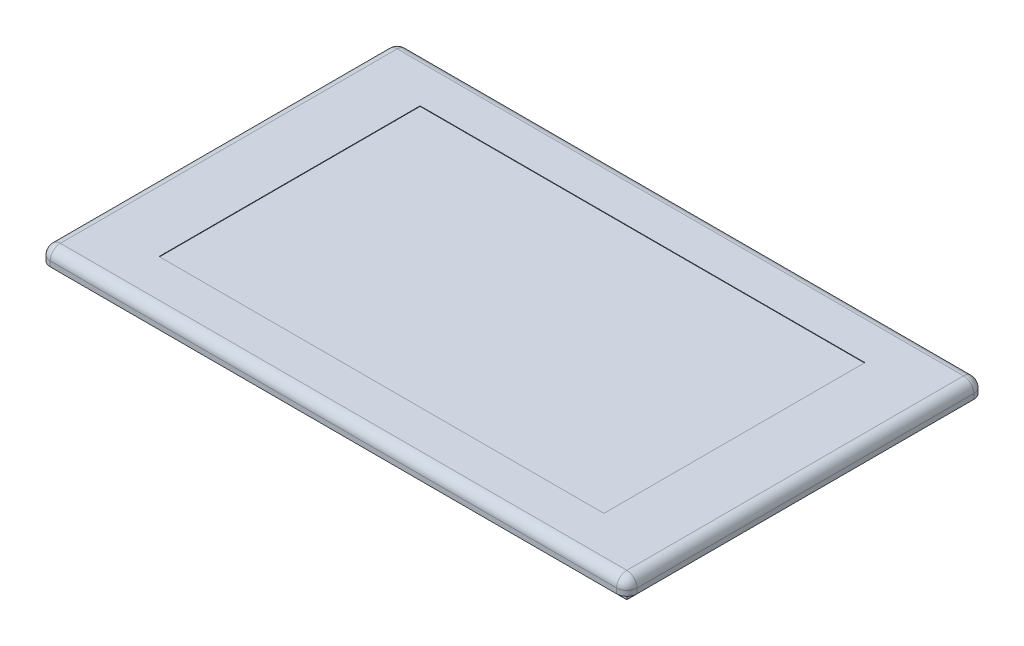
SolidWorks part; units mm, degrees
ref_plane "Front Plane" through (0, 0, 0) normal (0, 0, 1) x (1, 0, 0)
ref_plane "Top Plane" through (0, 0, 0) normal (0, 1, 0) x (1, 0, 0)
ref_plane "Right Plane" through (0, 0, 0) normal (1, 0, 0) x (0, 0, -1)
sketch "Sketch1" plane through (0, 0, 0) normal (0, 1, 0) x (1, 0, 0)
  line L1 (-57.5, 35) -> (57.5, 35)
  line L2 (-57.5, 35) -> (-57.5, -35)
  line L3 (-57.5, -35) -> (57.5, -35)
  line L4 (57.5, 35) -> (57.5, -35)
  line L5 (-57.5, 35) -> (57.5, -35) construction
  line L6 (-57.5, -35) -> (57.5, 35) construction
  point P0 (0, 0)
  dimension "D1" = 115
  dimension "D2" = 70
extrude "Boss-Extrude1" add sketch "Sketch1" along normal blind 3
sketch "Sketch2" plane through (0, 0, 0) normal (0, -1, 0) x (1, 0, 0)
  line L1 (54.5, 32) -> (-54.5, 32)
  line L2 (54.5, 32) -> (54.5, -32)
  line L3 (54.5, -32) -> (-54.5, -32)
  line L4 (-54.5, 32) -> (-54.5, -32)
  line L5 (54.5, 32) -> (-54.5, -32) construction
  line L6 (54.5, -32) -> (-54.5, 32) construction
  point P0 (0, 0)
  dimension "D1" = 64
  dimension "D2" = 109
extrude "Boss-Extrude2" add sketch "Sketch2" along normal blind 3
fillet "Fillet1" radius 2 8 edges at (0, 3, 35) (-57.5, 3, 0) (0, 3, -35) (57.5, 3, 0) (-57.5, 1.5, 35) (-57.5, 1.5, -35) (57.5, 1.5, -35) (57.5, 1.5, 35)
ref_plane "Plane1" through (55.5, 1, 35) normal (1, 0, 0) x (0, 0, -1)
sketch "Sketch4" plane through (0, 3, 0) normal (0, 1, 0) x (1, 0, 0)
  line L0 (55.5, 0) -> (-55.5, 0) construction
  line L1 (55.5, -33) -> (55.5, 33) construction
  line L2 (-55.5, 33) -> (-55.5, -33) construction
  line L3 (0, -33) -> (0, 33) construction
  line L4 (-55.5, -33) -> (55.5, -33) construction
  line L5 (55.5, 33) -> (-55.5, 33) construction
  line L7 (-43.5862, -25.5778) -> (43.5862, -25.5778)
  line L8 (-43.5862, -25.5778) -> (-43.5862, 25.5778)
  line L9 (-43.5862, 25.5778) -> (43.5862, 25.5778)
  line L10 (43.5862, -25.5778) -> (43.5862, 25.5778)
  line L11 (-43.5862, -25.5778) -> (43.5862, 25.5778) construction
  line L12 (-43.5862, 25.5778) -> (43.5862, -25.5778) construction
  point P12 (0, 0)
extrude "Cut-Extrude1" cut sketch "Sketch4" against normal blind 0.1
